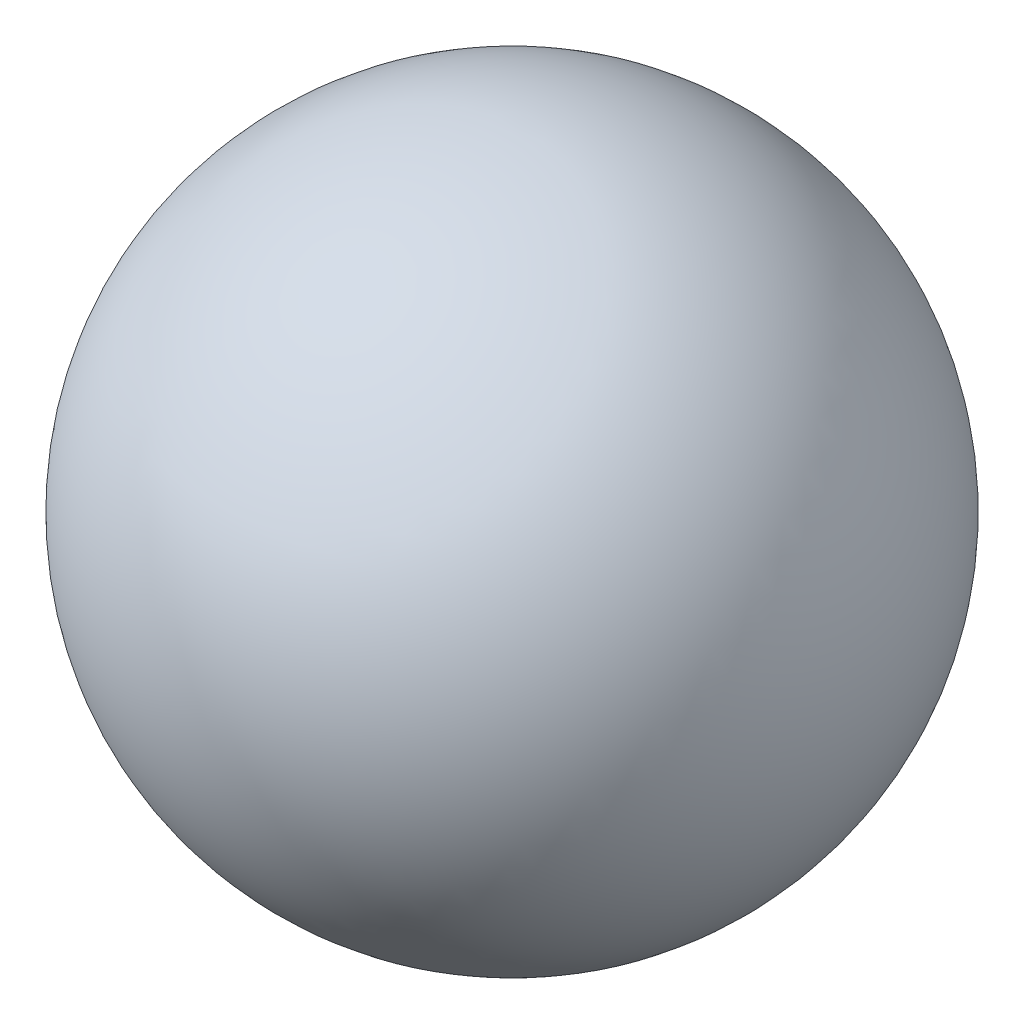
SolidWorks part; units mm, degrees
ref_plane "Front Plane" through (0, 0, 0) normal (0, 0, 1) x (1, 0, 0)
ref_plane "Top Plane" through (0, 0, 0) normal (0, 1, 0) x (1, 0, 0)
ref_plane "Right Plane" through (0, 0, 0) normal (1, 0, 0) x (0, 0, -1)
sketch "Sketch1" plane through (0, 0, 0) normal (0, 0, 1) x (1, 0, 0)
  line L0 (0, 35) -> (0, -35)
  arc A0 (0, 35) -> (0, -35) centre (0, 0) ccw
  dimension "D1" = 35
revolve "Revolve1" add sketch "Sketch1" angle 360 about L0
